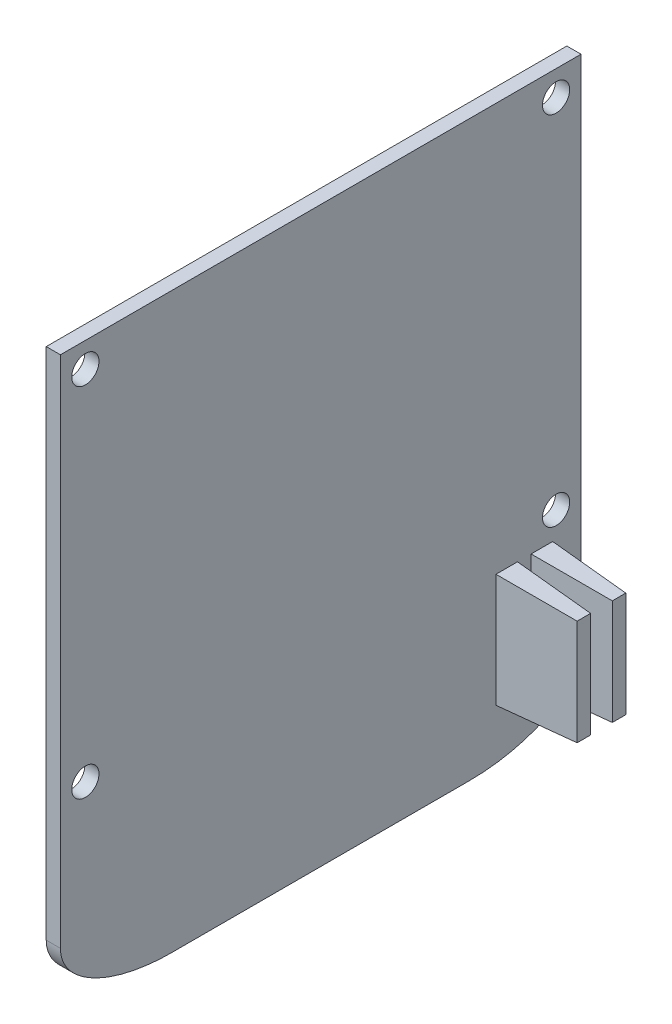
SolidWorks part; units mm, degrees
ref_plane "Front Plane" through (0, 0, 0) normal (0, 0, 1) x (1, 0, 0)
ref_plane "Top Plane" through (0, 0, 0) normal (0, 1, 0) x (1, 0, 0)
ref_plane "Right Plane" through (0, 0, 0) normal (1, 0, 0) x (0, 0, -1)
sketch "Sketch1" plane through (0, 0, 0) normal (1, 0, 0) x (0, 0, -1)
  line L0 (45.1827, 6.1807) -> (-13.0976, 6.1807)
  line L1 (45.1827, 6.1807) -> (45.1827, -39.4225)
  line L2 (45.1827, -39.4225) -> (45.1827, -51.3605)
  line L3 (32.6237, -58.0051) -> (-0.6503, -58.0051)
  line L5 (-13.0976, -51.3605) -> (-13.0976, 6.1807)
  ellipse E0 centre (32.6237, -51.3605) end of major axis (45.1827, -51.3605) minor radius 6.6446 (32.6237, -58.0051) -> (45.1827, -51.3605) ccw
  ellipse E1 centre (-0.6503, -51.3605) end of major axis (11.7969, -51.3605) minor radius 6.6446 (-13.0976, -51.3605) -> (-0.6503, -58.0051) ccw
  dimension "D1" = 58.2803
  dimension "D2" = 11.938
  dimension "D3" = 33.274
  dimension "D4" = 45.6032
extrude "Boss-Extrude1" add sketch "Sketch1" along normal blind 1.5875
sketch "Sketch2" plane through (0, 0, 0) normal (-1, 0, 0) x (0, 0, 1)
  circle A0 centre (-42.3887, 3.3867) radius 1.524
  circle A1 centre (10.3036, 3.3867) radius 1.524
  circle A2 centre (-42.3887, -36.6056) radius 1.524
  circle A3 centre (10.3036, -36.6056) radius 1.524
  dimension "D3" = 3.048
  dimension "D4" = 3.048
  dimension "D8" = 3.048
  dimension "D11" = 3.048
extrude "Cut-Extrude1" cut sketch "Sketch2" against normal blind 2.54
sketch "Sketch6" plane through (1.5875, 0, 0) normal (1, 0, 0) x (0, 0, -1)
  line L2 (42.0077, -39.4758) -> (42.0077, -52.1758)
  line L3 (42.0077, -52.1758) -> (39.5947, -52.1758)
  line L4 (35.6577, -52.1758) -> (35.6577, -39.4758)
  line L5 (42.0077, -39.4758) -> (39.5947, -39.4758)
  line L6 (35.6577, -39.4758) -> (38.0707, -39.4758)
  line L8 (38.0707, -39.4758) -> (38.0707, -52.1758)
  line L10 (39.5947, -52.1758) -> (39.5947, -39.4758)
  line L11 (38.0707, -52.1758) -> (35.6577, -52.1758)
  dimension "D3" = 12.7
  dimension "D4" = 6.35
  dimension "D5" = 2.413
  dimension "D6" = 2.413
extrude "Boss-Extrude2" add sketch "Sketch6" along normal blind 8.636 draft 3
